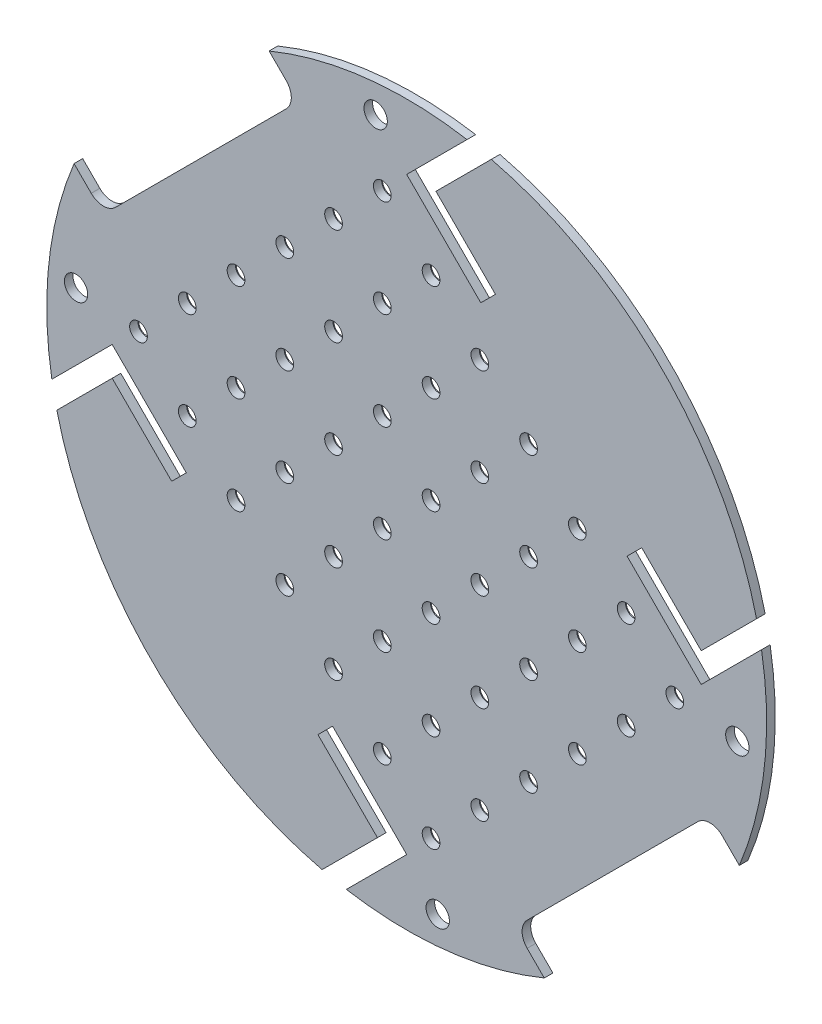
SolidWorks part; units mm, degrees
ref_plane "Front Plane" through (0, 0, 0) normal (0, 0, 1) x (1, 0, 0)
ref_plane "Top Plane" through (0, 0, 0) normal (0, 1, 0) x (1, 0, 0)
ref_plane "Right Plane" through (0, 0, 0) normal (1, 0, 0) x (0, 0, -1)
sketch "Sketch1" plane through (0, 0, 0) normal (0, 0, 1) x (1, 0, 0)
  circle A0 centre (0, 0) radius 66.294
  dimension "D1" = 132.588
extrude "Extrude1" add sketch "Sketch1" along normal blind 1.5875
sketch "Sketch2" plane through (0, 0, 1.5875) normal (0, 0, 1) x (1, 0, 0)
  line L0 (0, 0) -> (0, 66.294) construction
  line L1 (0, 66.294) -> (0, -66.294) construction
  line L2 (0, -66.294) -> (0, 0) construction
  line L3 (0, 0) -> (66.294, 0) construction
  line L4 (66.294, 0) -> (-66.294, 0) construction
  circle A0 centre (0, 0) radius 66.294 construction
sketch "Sketch6" plane through (0, 0, 1.5875) normal (0, 0, 1) x (1, 0, 0)
  line L0 (0, 66.294) -> (0, 51.308) construction
  line L1 (0, 0) -> (0, 66.294) construction
  dimension "D1" = 14.986
sketch "Sketch3" plane through (0, 0, 1.5875) normal (0, 0, 1) x (1, 0, 0)
  line L0 (0, 0) -> (12.1169, 0) construction
  line L1 (0, 0) -> (66.294, 0) construction
  line L2 (0, 54.2407) -> (54.2407, 0) construction
  line L3 (0, 0) -> (0, 54.2407) construction
  line L4 (0, 0) -> (0, 12.1169) construction
  line L5 (0, 0) -> (0, 66.294) construction
  line L6 (12.1803, 66.421) -> (66.421, 66.421)
  line L7 (0, 0) -> (54.2407, 0) construction
  line L8 (0, 54.2407) -> (12.1803, 66.421)
  line L9 (66.421, 66.421) -> (66.421, 12.1803)
  line L10 (54.2407, 0) -> (66.421, 12.1803)
  line L11 (0, 54.2407) -> (13.65, 40.5908)
  line L12 (13.65, 40.5908) -> (16.3441, 43.2848)
  line L13 (16.3441, 43.2848) -> (5.3882, 54.2407)
  line L14 (5.3882, 54.2407) -> (16.6545, 65.5071)
  line L15 (16.6545, 65.5071) -> (65.5071, 65.5071)
  line L16 (65.5071, 65.5071) -> (65.5071, 16.6545)
  line L17 (65.5071, 16.6545) -> (54.2407, 5.3882)
  line L18 (54.2407, 5.3882) -> (43.2848, 16.3441)
  line L19 (43.2848, 16.3441) -> (40.5908, 13.65)
  line L20 (40.5908, 13.65) -> (54.2407, 0)
  dimension "D1" = 76.708
  dimension "D2" = 3.81
  dimension "D3" = 3.81
  dimension "D4" = 38.1
extrude "Extrude2" cut sketch "Sketch3" against normal through all
pattern_circular "CirPattern1" count 2 over 180 about axis through (0, 0, 0) along (0, 0, 1) of "Extrude2"
sketch "Sketch11" plane through (0, 0, 0) normal (0, 0, -1) x (-1, 0, 0)
  line L0 (-66.294, 0) -> (-55.8604, 0) construction
  line L1 (-55.8604, 0) -> (-55.8604, -19.9394) construction
  line L2 (-55.8604, -19.9394) -> (-69.0112, -33.0902)
  line L3 (-69.0112, -33.0902) -> (-33.0902, -69.0112)
  line L4 (-33.0902, -69.0112) -> (-19.9394, -55.8604)
  line L5 (-19.9394, -55.8604) -> (-55.8604, -19.9394)
  line L6 (0, -66.294) -> (0, -55.8604) construction
  line L7 (0, -55.8604) -> (-19.9394, -55.8604) construction
  line L9 (-54.2407, 0) -> (-65.3556, 11.1149) construction
  arc A0 (-65.3556, 11.1149) -> (11.1149, -65.3556) centre (0, 0) ccw construction
  dimension "D1" = 50.8
extrude "Extrude3" cut sketch "Sketch11" against normal through all
sketch "Sketch8" plane through (0, 0, 1.5875) normal (0, 0, 1) x (1, 0, 0)
  line L0 (0, 66.294) -> (0, 60.8965) construction
  line L1 (0, 66.294) -> (0, 51.308) construction
  line L2 (0, 60.8965) -> (-5.715, 60.8965) construction
  line L3 (66.294, 0) -> (60.8965, 0) construction
  line L4 (60.8965, 0) -> (60.8965, -5.715) construction
  line L5 (0, -56.1023) -> (0, 56.1023) construction
  circle A0 centre (0, 0) radius 66.294 construction
  dimension "D1" = 5.3975
  dimension "D2" = 5.715
pattern_circular "CirPattern4" count 2 over 180 about axis through (0, 0, 0) along (0, 0, 1) of "Extrude3"
hole_wizard "#6 Clearance Hole1" positions "3DSketch3" profile "Sketch10" hole size "#6" standard "Ansi Inch" end condition through all
sketch3d "3DSketch3"
  point P0 (-5.715, 60.8965, 1.5875)
  point P3 (60.8965, -5.715, 1.5875)
sketch "Sketch10" plane through (-5.715, 60.8965, 1.5875) normal (1, 0, 0) x (0, -1, 0)
  line L0 (0, 0) -> (0, 1.5875)
  line L1 (0, 1.5875) -> (2.1526, 1.5875)
  line L2 (2.1526, 1.5875) -> (2.1526, 0)
  line L5 (2.1526, 0) -> (0, 0)
  line L11 (0, -6.35) -> (0, 107.95) construction
  dimension "Thru Hole Dia." = 4.3053
  dimension "Thru Hole Depth" = 1.5875
pattern_circular "CirPattern3" count 2 over 180 about axis through (0, 0, 0) along (0, 0, 1) of "#6 Clearance Hole1"
sketch "Sketch20" plane through (0, 0, 1.5875) normal (0, 0, 1) x (1, 0, 0)
  line L0 (0, 0) -> (-4.4901, -4.4901) construction
  line L1 (19.9394, -55.8604) -> (55.8604, -19.9394) construction
  dimension "D1" = 6.35
hole_wizard "#4 Clearance Hole1" positions "3DSketch9" profile "Sketch21" hole size "#4" standard "Ansi Inch"
sketch3d "3DSketch9"
  point P4 (-4.4901, -4.4901, 1.5875)
sketch "Sketch21" plane through (-4.4901, -4.4901, 1.5875) normal (1, 0, 0) x (0, -1, 0)
  line L0 (0, 0) -> (0, 2.5046)
  line L1 (0, 2.5046) -> (1.6319, 1.524)
  line L2 (1.6319, 1.524) -> (1.6319, 0)
  line L5 (1.6319, 0) -> (0, 0)
  line L10 (0, 2.5046) -> (-1.6319, 1.524) construction
  line L11 (0, -6.35) -> (0, 107.95) construction
  dimension "Hole Dia." = 3.2639
  dimension "Hole Depth" = 1.524
  dimension "Drill Angle" = 118
pattern_linear "LPattern1" count 3 spacing 12.7 along (-0.7071, -0.7071, 0) count 4 spacing 12.7 along (0.7071, 0.7071, 0) of "#4 Clearance Hole1"
pattern_linear "LPattern2" count 4 spacing 12.7 along (0.7071, -0.7071, 0) count 4 spacing 12.7 along (-0.7071, 0.7071, 0) of "LPattern1", "#4 Clearance Hole1"
fillet "Fillet1" radius 3.175 4 edges at (-55.8604, 19.9394, 0.7937) (-19.9394, 55.8604, 0.7937) (55.8604, -19.9394, 0.7937) (19.9394, -55.8604, 0.7937)
